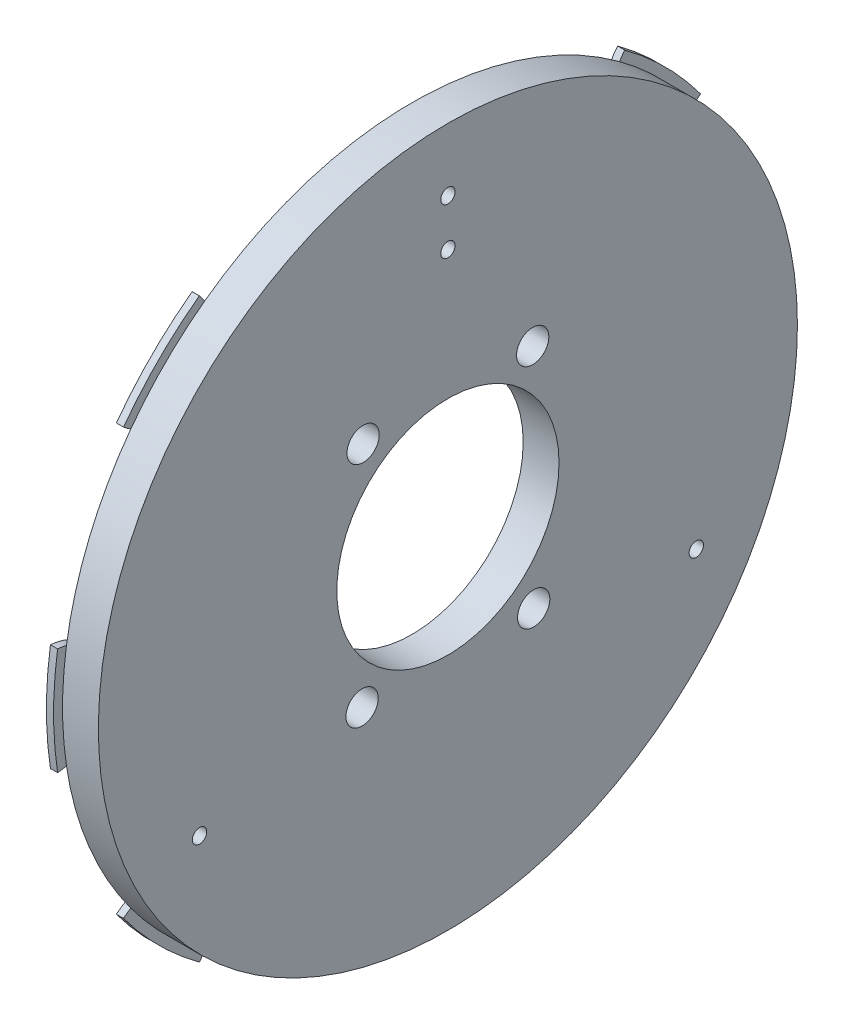
SolidWorks part; units mm, degrees
ref_plane "Front Plane" through (0, 0, 0) normal (0, 0, 1) x (1, 0, 0)
ref_plane "Top Plane" through (0, 0, 0) normal (0, 1, 0) x (1, 0, 0)
ref_plane "Right Plane" through (0, 0, 0) normal (1, 0, 0) x (0, 0, -1)
sketch "Sketch1" plane through (0, 0, 0) normal (1, 0, 0) x (0, 0, -1)
  circle A0 centre (0, 0) radius 97.5
  circle A1 centre (0, 0) radius 31
  circle A2 centre (0, 0) radius 39.675 construction
  circle A4 centre (23.65, 31.8557) radius 4.5
  circle A8 centre (23.9328, -31.6437) radius 4.5
  circle A10 centre (-23.9328, -31.6437) radius 4.5
  circle A14 centre (-23.65, 31.8557) radius 4.5
  circle A15 centre (0, 0) radius 80 construction
  circle A16 centre (0, 80) radius 2
  circle A17 centre (69.282, -40) radius 2
  circle A18 centre (-69.282, -40) radius 2
  point P5 (0, 0)
  point P6 (0, 0)
  point P12 (0, 0)
  point P13 (0, 0)
  point P14 (0, 0)
  point P15 (0, 0)
  point P16 (0, 0)
  point P17 (0, 0)
  point P20 (0, 0)
  point P21 (0, 0)
  point P24 (0, 0)
  point P32 (0, 0)
  point P40 (0, 0)
  dimension "D1" = 195
  dimension "D2" = 9
  dimension "D3" = 79.35
  dimension "D4" = 9
  dimension "D8" = 3
  dimension "D9" = 160
  dimension "D10" = 4
  dimension "D11" = 80
  dimension "D5" = 63.5
  dimension "D13" = 9
  dimension "D14" = 9
  dimension "D6" = 63.5
  dimension "D7" = 47.3
  dimension "D12" = 138.5641
extrude "Boss-Extrude1" add sketch "Sketch1" along normal blind 10 from offset 2
sketch "Sketch6" plane through (2, 0, 0) normal (-1, 0, 0) x (0, 0, 1)
  arc A0 (80.4919, 59.3385) -> (59.3385, 80.4919) centre (0, 0) ccw
  arc A1 (98.875, 14.9578) -> (98.875, -14.9578) centre (100, 0) ccw
  arc A2 (80.4919, -59.3385) -> (59.3385, -80.4919) centre (70.7107, -70.7107) ccw
  circle A3 centre (0, -100) radius 15 [skipped]
  arc A4 (-59.3385, -80.4919) -> (-80.4919, -59.3385) centre (-70.7107, -70.7107) ccw
  arc A5 (-98.875, -14.9578) -> (-98.875, 14.9578) centre (-100, 0) ccw
  arc A6 (-80.4919, 59.3385) -> (-59.3385, 80.4919) centre (-70.7107, 70.7107) ccw
  circle A7 centre (0, 100) radius 15 [skipped]
  arc A8 (59.3385, 80.4919) -> (80.4919, 59.3385) centre (70.7107, 70.7107) ccw
  arc A9 (-59.3385, 80.4919) -> (-80.4919, 59.3385) centre (0, 0) ccw
  arc A10 (-98.875, 14.9578) -> (-98.875, -14.9578) centre (0, 0) ccw
  arc A11 (-80.4919, -59.3385) -> (-59.3385, -80.4919) centre (0, 0) ccw
  arc A12 (59.3385, -80.4919) -> (80.4919, -59.3385) centre (0, 0) ccw
  arc A13 (98.875, -14.9578) -> (98.875, 14.9578) centre (0, 0) ccw
  point P22 (0, 0)
  dimension "D1" = 8
  dimension "D3" = 15
  dimension "D5" = 200
  dimension "D2" = 100
  dimension "D4" = 100
extrude "Boss-Extrude2" add sketch "Sketch6" along normal blind 2
sketch "Sketch7" plane through (2, 0, 0) normal (-1, 0, 0) x (0, 0, 1)
  line L0 (0, 0) -> (0, 67) construction
  circle A1 centre (0, 67) radius 2
  dimension "D1" = 67
extrude "Cut-Extrude1" cut sketch "Sketch7" against normal blind 10
sketch "Sketch8" plane through (0, 0, 0) normal (0, 0, 1) x (1, 0, 0)
  line L0 (-21, -60.5) -> (3.2125, -60.5)
  line L1 (3.2125, -60.5) -> (3.2125, -71.5)
  line L2 (3.2125, -71.5) -> (-21, -71.5)
  circle A0 centre (-21, -66) radius 5
  arc A1 (-21, -60.5) -> (-21, -71.5) centre (-21, -66) ccw
  dimension "D1" = 11
extrude "Boss-Extrude3" add sketch "Sketch8" along normal mid plane 25
